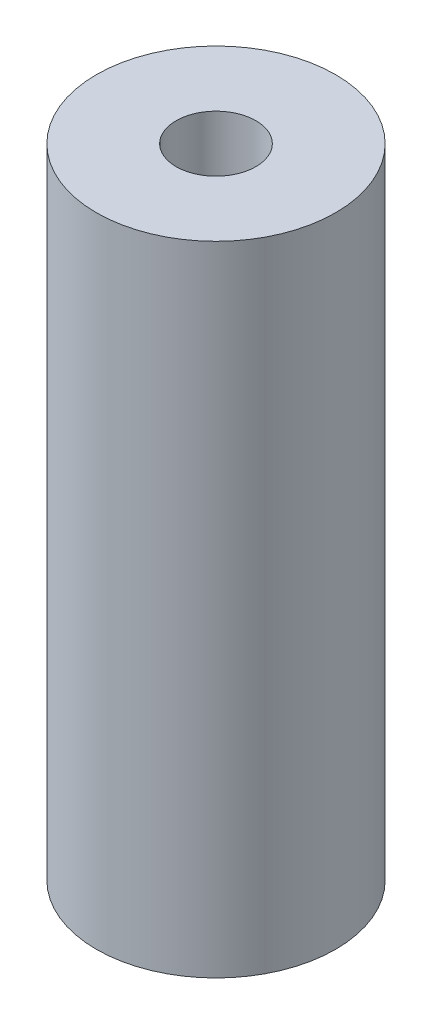
SolidWorks part; units mm, degrees
ref_plane "前视基准面" through (0, 0, 0) normal (0, 0, 1) x (1, 0, 0)
ref_plane "上视基准面" through (0, 0, 0) normal (0, 1, 0) x (1, 0, 0)
ref_plane "右视基准面" through (0, 0, 0) normal (1, 0, 0) x (0, 0, -1)
sketch "Sketch1" plane through (0, 0, 0) normal (0, 1, 0) x (1, 0, 0)
  circle A0 centre (0, 0) radius 1.5
  circle A1 centre (0, 0) radius 4.5
extrude "Boss-Extrude1" add sketch "Sketch1" along normal blind 24
